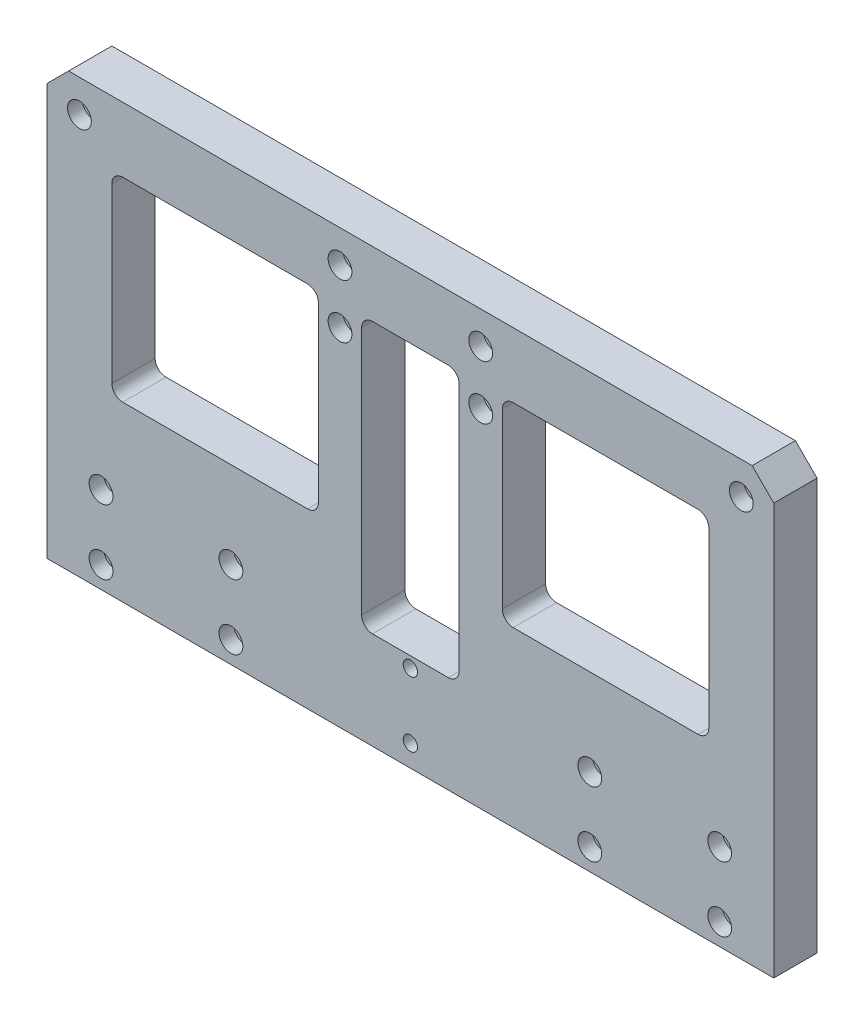
SolidWorks part; units mm, degrees
material "6061 Alloy"
ref_plane "Front Plane" through (0, 0, 0) normal (0, 0, 1) x (1, 0, 0)
ref_plane "Top Plane" through (0, 0, 0) normal (0, 1, 0) x (1, 0, 0)
ref_plane "Right Plane" through (0, 0, 0) normal (1, 0, 0) x (0, 0, -1)
sketch "Sketch1" plane through (0, 0, 0) normal (0, 0, 1) x (1, 0, 0)
  line L1 (167.9, 100) -> (-167.9, 100)
  line L2 (167.9, 100) -> (167.9, -100)
  line L3 (167.9, -100) -> (-167.9, -100)
  line L4 (-167.9, 100) -> (-167.9, -100)
  line L5 (167.9, 100) -> (-167.9, -100) construction
  line L6 (167.9, -100) -> (-167.9, 100) construction
  point P0 (0, 0)
  dimension "D1" = 335.8
  dimension "D2" = 200
extrude "Boss-Extrude1" add sketch "Sketch1" along normal blind 20 contours L4 L3 L2 L1
sketch "Sketch2" plane through (0, 0, 20) normal (0, 0, 1) x (1, 0, 0)
  line L0 (167.9, 100) -> (-167.9, 100) construction
  line L1 (137.9, -20) -> (-137.9, -20)
  line L2 (137.9, -20) -> (137.9, 70)
  line L3 (137.9, 70) -> (-137.9, 70)
  line L4 (-137.9, -20) -> (-137.9, 70)
  line L5 (137.9, -20) -> (-137.9, 70) construction
  line L6 (137.9, 70) -> (-137.9, -20) construction
  line L7 (167.9, -100) -> (-167.9, -100) construction
  line L8 (-167.9, 100) -> (-167.9, -100) construction
  point P0 (0, 25)
  dimension "D1" = 30
  dimension "D2" = 80
  dimension "D3" = 30
extrude "Cut-Extrude1" cut sketch "Sketch2" against normal through all
sketch "Sketch3" plane through (0, 0, 0) normal (0, 0, -1) x (-1, 0, 0)
  line L0 (-167.9, -100) -> (167.9, -100) construction
  line L1 (22.5, 35) -> (-22.5, 35)
  line L2 (22.5, 35) -> (22.5, -55)
  line L3 (22.5, -55) -> (-22.5, -55)
  line L4 (-22.5, 35) -> (-22.5, -55)
  line L5 (22.5, 35) -> (-22.5, -55) construction
  line L6 (22.5, -55) -> (-22.5, 35) construction
  point P0 (0, -10)
  dimension "D1" = 45
  dimension "D2" = 45
  dimension "D3" = 90
extrude "Cut-Extrude2" cut sketch "Sketch3" against normal through all
hole_wizard "CBORE for M6 Hexagon socket head cap screws1" positions "Sketch4" profile "Sketch5" counterbore size "M6" standard "GB" end condition through all
sketch "Sketch4" plane through (0, 0, 20) normal (0, 0, 1) x (1, 0, 0)
  line L0 (0, -11) -> (0, 11) construction
  line L1 (-167.9, 100) -> (-167.9, -100) construction
  line L2 (167.9, -100) -> (-167.9, -100) construction
  point P0 (-142.9, -60)
  point P2 (-142.9, -90)
  point P4 (-82.9, -60)
  point P6 (-82.9, -90)
  point P15 (82.9, -90)
  point P16 (82.9, -60)
  point P17 (142.9, -90)
  point P18 (142.9, -60)
  dimension "D1" = 30
  dimension "D2" = 60
  dimension "D3" = 25
  dimension "D4" = 10
sketch "Sketch5" plane through (-142.9, -60, 20) normal (1, 0, 0) x (0, -1, 0)
  line L0 (0, 0) -> (0, 20)
  line L1 (0, 20) -> (3.3, 20)
  line L3 (3.3, 20) -> (3.3, 6.8)
  line L4 (3.3, 6.8) -> (5.5, 6.8)
  line L5 (5.5, 6.8) -> (5.5, 0)
  line L7 (5.5, 0) -> (0, 0)
  line L11 (0, -6.35) -> (0, 107.95) construction
  dimension "Thru Hole Dia." = 6.6
  dimension "Thru Hole Depth" = 20
  dimension "C'Bore Dia." = 11
  dimension "C'Bore Depth" = 6.8
hole_wizard "M6 Clearance Hole1" positions "Sketch6" profile "Sketch7" hole size "M6" standard "GB" end condition through all
sketch "Sketch6" plane through (0, 0, 20) normal (0, 0, 1) x (1, 0, 0)
  point P0 (0, -60)
  point P2 (0, -90)
sketch "Sketch7" plane through (0, -60, 20) normal (1, 0, 0) x (0, -1, 0)
  line L0 (0, 0) -> (0, 20)
  line L1 (0, 20) -> (3.3, 20)
  line L2 (3.3, 20) -> (3.3, 0)
  line L5 (3.3, 0) -> (0, 0)
  line L11 (0, -6.35) -> (0, 107.95) construction
  dimension "Thru Hole Dia." = 6.6
  dimension "Thru Hole Depth" = 20
sketch "Sketch8" plane through (0, 0, 20) normal (0, 0, 1) x (1, 0, 0)
  line L0 (137.9, 70) -> (-137.9, 70) construction
  line L1 (-22.5, -20) -> (-42.5, -20)
  line L2 (-22.5, -20) -> (-22.5, 70)
  line L3 (-22.5, 70) -> (-42.5, 70)
  line L4 (-42.5, -20) -> (-42.5, 70)
  line L5 (0, -11) -> (0, 11) construction
  line L6 (22.5, 70) -> (42.5, 70)
  line L7 (42.5, -20) -> (42.5, 70)
  line L8 (22.5, -20) -> (42.5, -20)
  line L9 (22.5, -20) -> (22.5, 70)
  dimension "D1" = 20
extrude "Boss-Extrude2" add sketch "Sketch8" against normal up to surface (20 mm away) up to face at (3.3, -60, 0)
fillet "Fillet1" radius 5 12 edges at (-137.9, -20, 10) (-137.9, 70, 10) (137.9, 70, 10) (137.9, -20, 10) (-22.5, -55, 10) (22.5, -55, 10) (42.5, -20, 10) (42.5, 70, 10) (22.5, 70, 10) (-22.5, 70, 10) (-42.5, -20, 10) (-42.5, 70, 10)
hole_wizard "CBORE for M6 Hexagon socket head cap screws2" positions "Sketch11" profile "Sketch10" counterbore size "M6" standard "GB" end condition through all
sketch "Sketch11" plane through (0, 0, 20) normal (0, 0, 1) x (1, 0, 0)
  line L0 (0, -11) -> (0, 11) construction
  line L1 (-167.9, 100) -> (-167.9, -100) construction
  line L2 (167.9, 100) -> (-167.9, 100) construction
  point P0 (-152.9, 85)
  point P2 (-32.5, 60)
  point P4 (-32.5, 85)
  point P9 (32.5, 85)
  point P10 (32.5, 60)
  point P11 (152.9, 85)
  dimension "D1" = 15
  dimension "D2" = 25
  dimension "D3" = 15
  dimension "D4" = 65
sketch "Sketch10" plane through (-152.9, 85, 20) normal (1, 0, 0) x (0, -1, 0)
  line L0 (0, 0) -> (0, 20)
  line L1 (0, 20) -> (3.3, 20)
  line L3 (3.3, 20) -> (3.3, 6.8)
  line L4 (3.3, 6.8) -> (5.5, 6.8)
  line L5 (5.5, 6.8) -> (5.5, 0)
  line L7 (5.5, 0) -> (0, 0)
  line L11 (0, -6.35) -> (0, 107.95) construction
  dimension "Thru Hole Dia." = 6.6
  dimension "Thru Hole Depth" = 20
  dimension "C'Bore Dia." = 11
  dimension "C'Bore Depth" = 6.8
chamfer "Chamfer1" distance 10 angle 45 2 edges at (167.9, 100, 10) (-167.9, 100, 10)
